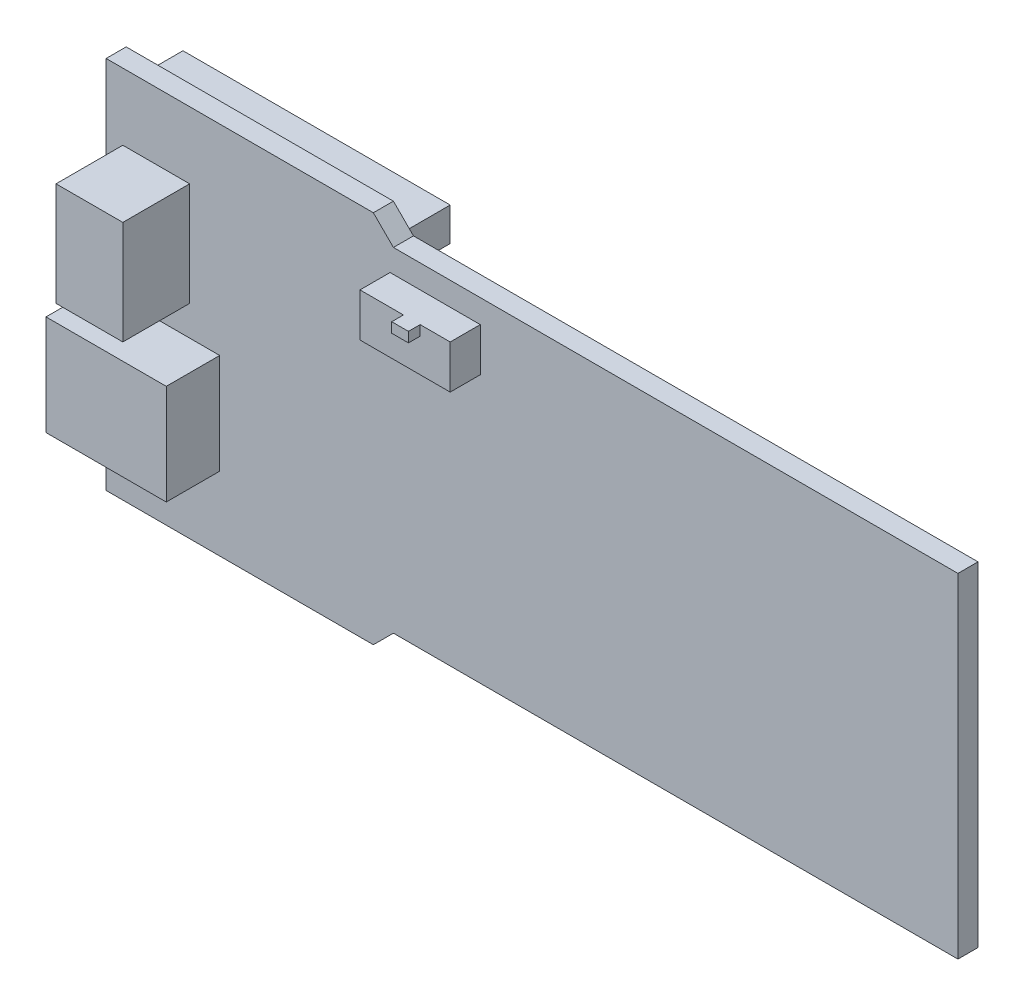
SolidWorks part; units mm, degrees
ref_plane "Front Plane" through (0, 0, 0) normal (0, 0, 1) x (1, 0, 0)
ref_plane "Top Plane" through (0, 0, 0) normal (0, 1, 0) x (1, 0, 0)
ref_plane "Right Plane" through (0, 0, 0) normal (1, 0, 0) x (0, 0, -1)
sketch "Sketch1" plane through (0, 0, 0) normal (0, 0, 1) x (1, 0, 0)
  line L0 (0, 0) -> (-32.3804, 0) construction
  line L1 (-10.5364, -12.7) -> (32.3896, -12.7)
  line L2 (-32.3804, -12.6964) -> (-32.3804, 12.6964) construction
  line L3 (-10.5364, 12.7) -> (32.3896, 12.7)
  line L4 (32.3896, -12.7) -> (32.3896, 12.7)
  line L5 (-32.3804, -12.6964) -> (32.3896, 12.7) construction
  line L6 (-32.3804, 12.6964) -> (32.3896, -12.7) construction
  line L7 (-32.3804, -14.224) -> (-12.0604, -14.224)
  line L8 (-32.3804, -14.224) -> (-32.3804, 14.224)
  line L9 (-32.3804, 14.224) -> (-12.0604, 14.224)
  line L11 (-12.0604, 14.224) -> (-10.5364, 12.7)
  line L12 (-12.0604, -14.224) -> (-10.5364, -12.7)
  point P0 (0, 0)
  dimension "D1" = 64.77
  dimension "D2" = 25.4
  dimension "D3" = 28.448
  dimension "D4" = 20.32
  dimension "D5" = 135
  dimension "D6" = 135
extrude "Boss-Extrude1" add sketch "Sketch1" along normal blind 1.524
sketch "Sketch2" plane through (0, 0, 1.524) normal (0, 0, 1) x (1, 0, 0)
  line L1 (-32.8884, -8.636) -> (-23.7444, -8.636)
  line L2 (-32.8884, -8.636) -> (-32.8884, -1.016)
  line L3 (-32.8884, -1.016) -> (-23.7444, -1.016)
  line L4 (-23.7444, -8.636) -> (-23.7444, -1.016)
  line L5 (-32.3804, -14.224) -> (-12.0604, -14.224) construction
  line L6 (-32.3804, 14.224) -> (-32.3804, -14.224) construction
  dimension "D1" = 7.62
  dimension "D2" = 5.588
  dimension "D3" = 9.144
  dimension "D4" = 0.508
extrude "Boss-Extrude2" add sketch "Sketch2" along normal blind 4.064
sketch "Sketch3" plane through (0, 0, 1.524) normal (0, 0, 1) x (1, 0, 0)
  line L1 (-31.1104, 1.27) -> (-26.0304, 1.27)
  line L2 (-31.1104, 1.27) -> (-31.1104, 9.144)
  line L3 (-31.1104, 9.144) -> (-26.0304, 9.144)
  line L4 (-26.0304, 1.27) -> (-26.0304, 9.144)
  line L5 (-12.0604, 14.224) -> (-32.3804, 14.224) construction
  line L6 (-32.3804, 14.224) -> (-32.3804, -1.016) construction
  dimension "D1" = 7.874
  dimension "D2" = 5.08
  dimension "D3" = 5.08
  dimension "D4" = 1.27
extrude "Boss-Extrude3" add sketch "Sketch3" along normal blind 5.08
sketch "Sketch4" plane through (0, 0, 0) normal (0, 0, -1) x (-1, 0, 0)
  line L0 (32.3804, 14.224) -> (32.3804, -14.224) construction
  line L1 (31.8724, 12.319) -> (11.5524, 12.319)
  line L2 (31.8724, 12.319) -> (31.8724, 9.779)
  line L3 (31.8724, 9.779) -> (11.5524, 9.779)
  line L4 (11.5524, 12.319) -> (11.5524, 9.779)
  line L5 (12.0604, 14.224) -> (32.3804, 14.224) construction
  dimension "D1" = 20.32
  dimension "D2" = 2.54
  dimension "D3" = 0.508
  dimension "D4" = 1.905
extrude "Boss-Extrude4" add sketch "Sketch4" along normal blind 3.81
mirror "Mirror1" about plane through (0, 0, 0) normal (0, 1, 0) of "Boss-Extrude4"
sketch "Sketch6" plane through (0, 0, 1.524) normal (0, 0, 1) x (1, 0, 0)
  line L0 (-32.3804, 14.224) -> (-32.3804, -1.016) construction
  line L1 (-10.7904, 7.62) -> (-3.9324, 7.62)
  line L2 (-10.7904, 7.62) -> (-10.7904, 10.922)
  line L3 (-10.7904, 10.922) -> (-3.9324, 10.922)
  line L4 (-3.9324, 7.62) -> (-3.9324, 10.922)
  line L5 (32.3896, 12.7) -> (-10.5364, 12.7) construction
  dimension "D1" = 21.59
  dimension "D2" = 3.302
  dimension "D3" = 6.858
  dimension "D4" = 1.778
extrude "Boss-Extrude5" add sketch "Sketch6" along normal blind 2.286
sketch "Sketch7" plane through (0, 0, 3.81) normal (0, 0, 1) x (1, 0, 0)
  line L0 (-3.9324, 10.922) -> (-10.7904, 10.922) construction
  line L1 (-6.2184, 10.922) -> (-7.4884, 10.922)
  line L2 (-6.2184, 10.922) -> (-6.2184, 10.16)
  line L3 (-6.2184, 10.16) -> (-7.4884, 10.16)
  line L4 (-7.4884, 10.922) -> (-7.4884, 10.16)
  line L5 (-10.7904, 10.922) -> (-10.7904, 7.62) construction
  dimension "D1" = 3.302
  dimension "D2" = 0.762
  dimension "D3" = 1.27
extrude "Boss-Extrude6" add sketch "Sketch7" along normal blind 0.889
